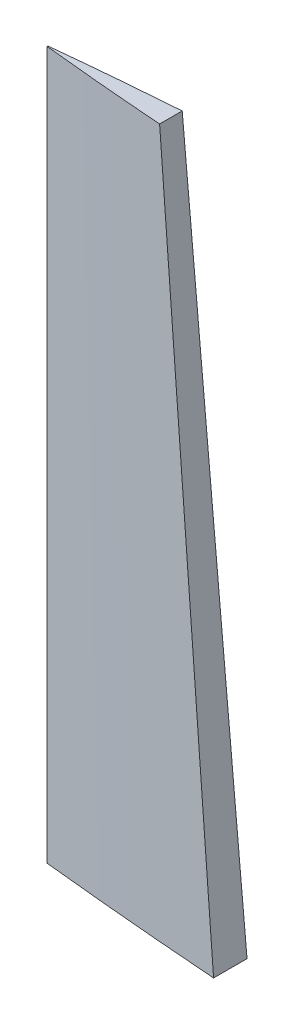
SolidWorks part; units mm, degrees
ref_plane "Front Plane" through (0, 0, 0) normal (0, 0, 1) x (1, 0, 0)
ref_plane "Top Plane" through (0, 0, 0) normal (0, 1, 0) x (1, 0, 0)
ref_plane "Right Plane" through (0, 0, 0) normal (1, 0, 0) x (0, 0, -1)
ref_plane "Plane1" through (0, 22, 0) normal (0, 1, 0) x (1, 0, 0)
sketch "Sketch1" plane through (0, 22, 0) normal (0, 1, 0) x (1, 0, 0)
  line L0 (-118.3161, 4.4015) -> (-118.3161, -4.4015)
  line L1 (-166.383, 0.1514) -> (-166.383, -0.1514)
  spline S0 degree 3 poles (-118.3161, 4.4015) (-118.496, 4.3888) (-121.1673, 4.2003) (-126.1821, 3.812) (-133.1891, 3.2525) (-139.6818, 2.7033) (-145.5894, 2.1811) (-150.8471, 1.6969) (-155.3973, 1.2627) (-159.1901, 0.8894) (-162.1841, 0.5871) (-164.3463, 0.3645) (-165.6532, 0.2281) (-166.2367, 0.1668) (-166.383, 0.1514) knots 0 0 0 0 0.011212 0.166483 0.312686 0.448211 0.571563 0.681381 0.776452 0.855723 0.918312 0.963525 0.990856 1 1 1 1
  spline S1 degree 3 poles (-118.3161, -4.4015) (-118.496, -4.3888) (-121.1673, -4.2003) (-126.1821, -3.812) (-133.1891, -3.2525) (-139.6818, -2.7033) (-145.5894, -2.1811) (-150.8471, -1.6969) (-155.3973, -1.2627) (-159.1901, -0.8894) (-162.1841, -0.5871) (-164.3463, -0.3645) (-165.6532, -0.2281) (-166.2367, -0.1668) (-166.383, -0.1514) knots 0 0 0 0 0.011212 0.166483 0.312686 0.448211 0.571563 0.681381 0.776452 0.855723 0.918312 0.963525 0.990856 1 1 1 1
ref_plane "Plane2" through (0, 207.979, 0) normal (0, 1, 0) x (1, 0, 0)
sketch "Sketch2" plane through (0, 207.979, 0) normal (0, 1, 0) x (1, 0, 0)
  line L0 (-133.9383, 2.971) -> (-133.9383, -2.971)
  line L1 (-166.383, 0.1022) -> (-166.383, -0.1022)
  spline S0 degree 3 poles (-133.9383, 2.971) (-134.0597, 2.9624) (-135.8629, 2.8352) (-139.2478, 2.573) (-143.9774, 2.1954) (-148.36, 1.8247) (-152.3476, 1.4722) (-155.8964, 1.1454) (-158.9678, 0.8523) (-161.5279, 0.6003) (-163.5488, 0.3963) (-165.0083, 0.246) (-165.8904, 0.154) (-166.2843, 0.1126) (-166.383, 0.1022) knots 0 0 0 0 0.011212 0.166483 0.312686 0.448211 0.571563 0.681381 0.776452 0.855723 0.918312 0.963525 0.990856 1 1 1 1
  spline S1 degree 3 poles (-133.9383, -2.971) (-134.0597, -2.9624) (-135.8629, -2.8352) (-139.2478, -2.573) (-143.9774, -2.1954) (-148.36, -1.8247) (-152.3476, -1.4722) (-155.8964, -1.1454) (-158.9678, -0.8523) (-161.5279, -0.6003) (-163.5488, -0.3963) (-165.0083, -0.246) (-165.8904, -0.154) (-166.2843, -0.1126) (-166.383, -0.1022) knots 0 0 0 0 0.011212 0.166483 0.312686 0.448211 0.571563 0.681381 0.776452 0.855723 0.918312 0.963525 0.990856 1 1 1 1
loft "Loft1" add profiles "Sketch1", "Sketch2"
